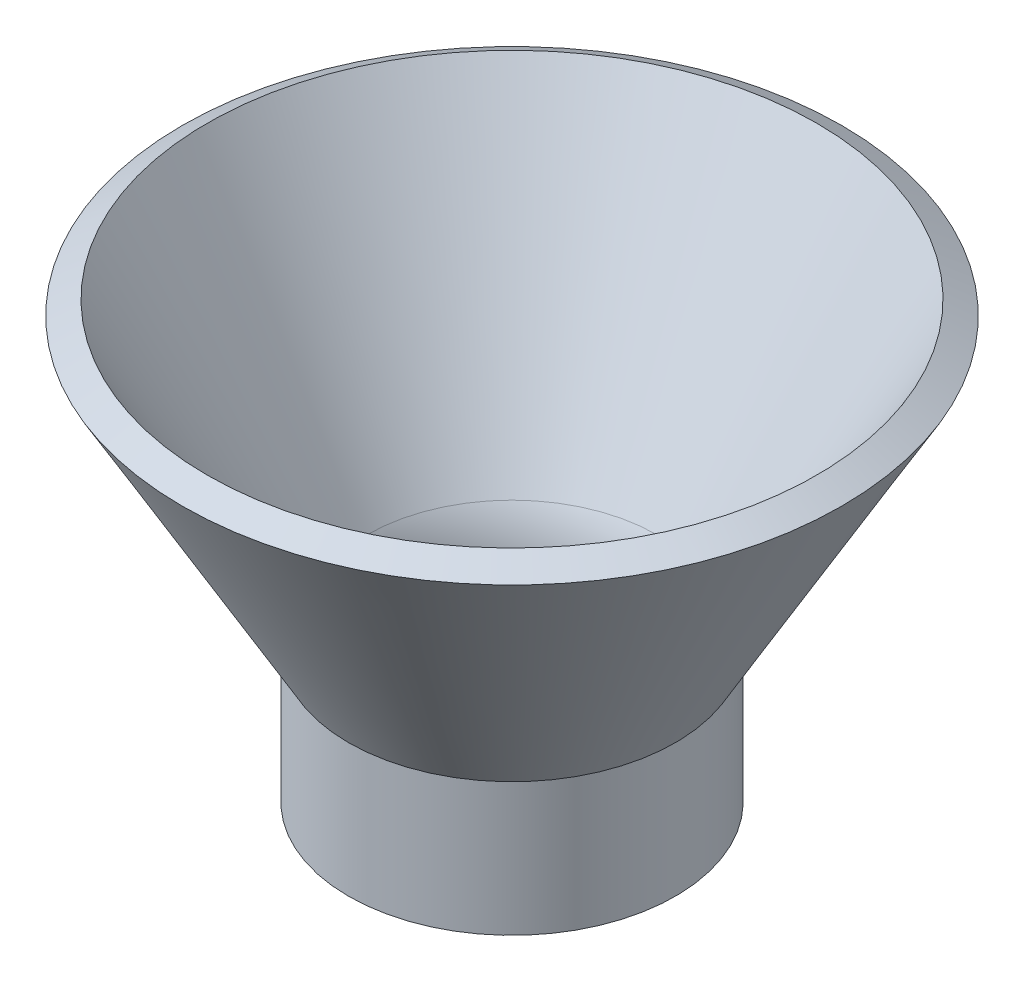
SolidWorks part; units mm, degrees
ref_plane "Front Plane" through (0, 0, 0) normal (0, 0, 1) x (1, 0, 0)
ref_plane "Top Plane" through (0, 0, 0) normal (0, 1, 0) x (1, 0, 0)
ref_plane "Right Plane" through (0, 0, 0) normal (1, 0, 0) x (0, 0, -1)
sketch "Sketch1" plane through (0, 0, 0) normal (0, 1, 0) x (1, 0, 0)
  circle A0 centre (0, 0) radius 14.75
  circle A1 centre (0, 0) radius 11.75
  dimension "D1" = 29.5
  dimension "D2" = 3
extrude "Boss-Extrude1" add sketch "Sketch1" along normal blind 12
sketch "Sketch2" plane through (0, 0, 0) normal (0, 0, 1) x (1, 0, 0)
  line L0 (0, 0) -> (0, 29.4274) construction
  line L1 (-14.75, 12) -> (-29.75, 37.9808)
  line L2 (-29.75, 37.9808) -> (-27.5, 39.2798)
  line L3 (-27.5, 39.2798) -> (-11.75, 12)
  line L4 (-11.75, 12) -> (-14.75, 12)
  line L5 (-14.75, 12) -> (-14.75, 42.4912) construction
  point P10 (0, 0)
  point P13 (-11.8, 12)
  dimension "D1" = 30
  dimension "D2" = 30
revolve "Revolve1" add sketch "Sketch2" angle 360 about L0
fillet "Fillet1" radius 10 1 edges at (0, 12, -11.75)
